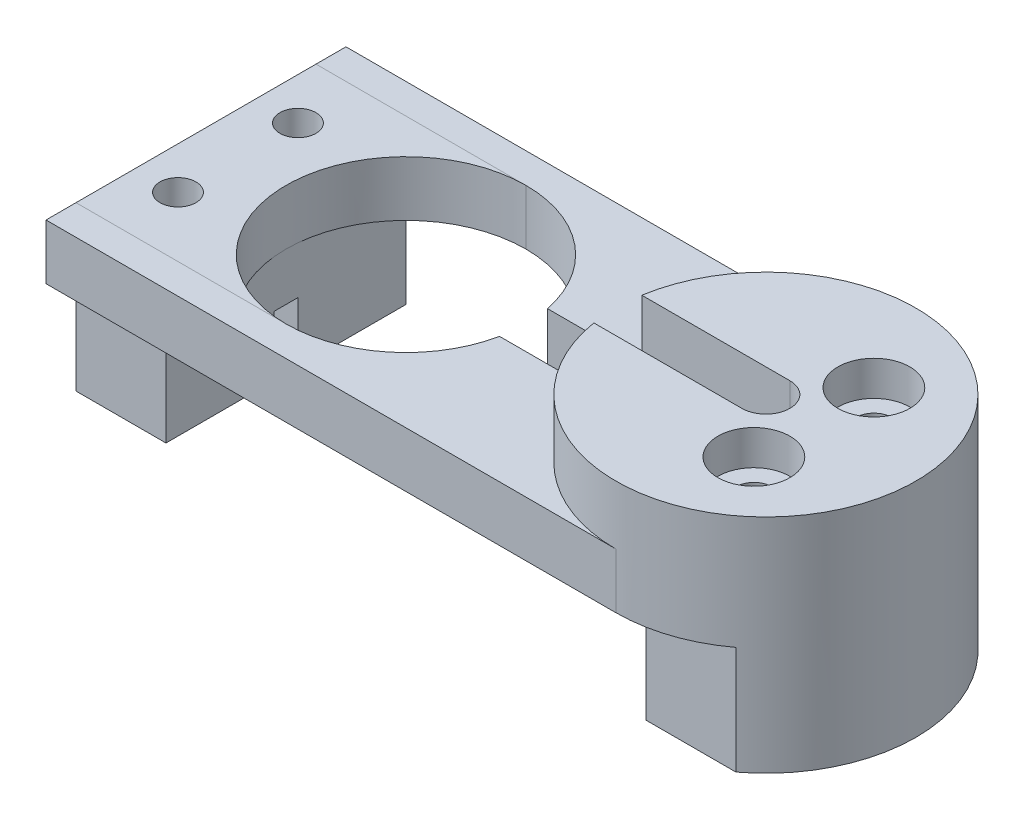
SolidWorks part; units mm, degrees
ref_plane "前视基准面" through (0, 0, 0) normal (0, 0, 1) x (1, 0, 0)
ref_plane "上视基准面" through (0, 0, 0) normal (0, 1, 0) x (1, 0, 0)
ref_plane "右视基准面" through (0, 0, 0) normal (1, 0, 0) x (0, 0, -1)
other "Configuration Table"
sketch "草图1" plane through (0, 0, 0) normal (0, 1, 0) x (1, 0, 0)
  line L0 (-20, 0) -> (20, 0) construction
  line L1 (-20, 10) -> (20, 10)
  line L2 (-20, 10) -> (-20, -10)
  line L3 (-20, -10) -> (20, -10)
  line L4 (20, 10) -> (20, -10)
  line L5 (-20, 10) -> (20, -10) construction
  line L6 (-20, -10) -> (20, 10) construction
  point P0 (0, 0)
  dimension "D1" = 40
  dimension "D2" = 20
extrude "凸台-拉伸1" add sketch "草图1" along normal blind 4.6
sketch "草图2" plane through (0, 0, 0) normal (0, -1, 0) x (1, 0, 0)
  line L0 (-20, 0) -> (20, 0) construction
  line L1 (-20, -10) -> (-20, 10) construction
  line L2 (20, 10) -> (20, -10) construction
  circle A0 centre (-10, 0) radius 6.5
  dimension "D1" = 13
  dimension "D2" = 10
extrude "切除-拉伸1" cut sketch "草图2" against normal blind 2
sketch "草图4" plane through (0, 2, 0) normal (0, -1, 0) x (1, 0, 0)
  circle A0 centre (-10, 0) radius 5.5
  dimension "D1" = 11
extrude "切除-拉伸5" cut sketch "草图4" against normal blind 2.6
sketch "草图5" plane through (0, 0, 0) normal (0, -1, 0) x (1, 0, 0)
  line L0 (20, 10) -> (20, -10) construction
  circle A0 centre (20, 0) radius 12.5
  dimension "D1" = 25
extrude "凸台-拉伸2" add sketch "草图5" against normal blind 9.5
sketch "草图6" plane through (0, 0, 0) normal (0, -1, 0) x (1, 0, 0)
  circle A0 centre (20, 0) radius 4.5
  dimension "D1" = 9
extrude "切除-拉伸6" cut sketch "草图6" against normal blind 4
sketch "草图7" plane through (0, 4, 0) normal (0, -1, 0) x (1, 0, 0)
  circle A0 centre (20, 0) radius 2
  dimension "D1" = 4
extrude "切除-拉伸7" cut sketch "草图7" against normal through all
sketch "草图8" plane through (0, 0, 0) normal (0, -1, 0) x (1, 0, 0)
  line L0 (20, -4.5) -> (20, -10) construction
  line L1 (-20, 10) -> (-27.5, 10)
  line L2 (-20, 10) -> (-20, -10)
  line L3 (-20, -10) -> (-27.5, -10)
  line L4 (-27.5, 10) -> (-27.5, -10)
  line L5 (12.5, 10) -> (20, 10) construction
  line L6 (12.5, 10) -> (12.5, -10) construction
  line L7 (12.5, -10) -> (20, -10) construction
  line L8 (20, 10) -> (20, 4.5) construction
  line L9 (20, -4.5) -> (20, -10)
  line L10 (20, 10) -> (27.5, 10)
  line L11 (20, 10) -> (20, 4.5)
  line L12 (20, -10) -> (27.5, -10)
  line L14 (-20, 0) -> (-27.5, 0) construction
  arc A1 (12.5, -10) -> (12.5, 10) centre (20, 0) ccw construction
  arc A2 (20, -4.5) -> (20, 4.5) centre (20, 0) ccw
  arc A3 (27.5, -10) -> (27.5, 10) centre (20, 0) ccw
  point P27 (-25, 0)
  dimension "D1" = 7.5
  dimension "D2" = 7.5
extrude "凸台-拉伸4" add sketch "草图8" along normal blind 9 and the other way blind 4.6
sketch "草图9" plane through (0, -9, 0) normal (0, -1, 0) x (1, 0, 0)
  line L0 (-27.5, 0) -> (-20, 0) construction
  line L1 (-25, 1) -> (-20, 1)
  line L2 (-25, 1) -> (-25, -1)
  line L3 (-25, -1) -> (-20, -1)
  line L4 (-20, 1) -> (-20, -1)
  line L5 (-27.5, 10) -> (-27.5, -10) construction
  line L7 (-20, -10) -> (-20, 10) construction
  line L8 (-20, 10) -> (20, 10)
  line L9 (20, 10) -> (20, 4.5) construction
  line L10 (0, 10) -> (0, 0) construction
  line L11 (25, -1) -> (20, -1)
  line L12 (20, 1) -> (20, -1)
  line L13 (25, 1) -> (20, 1)
  line L14 (25, 1) -> (25, -1)
  point P8 (-25, 0)
  line M7 (-20, -10) -> (-20, 10)
  dimension "D1" = 5
  dimension "D2" = 2
extrude "切除-拉伸8" cut sketch "草图9" against normal blind 5 contours L2 L3 L1 M7 | L14 L13 L12 L11
sketch "草图10" plane through (0, -9, 0) normal (0, -1, 0) x (1, 0, 0)
  line L0 (-20, -10) -> (-20, 10) construction
  line L1 (-20, -10) -> (-20, 10) construction
  line L2 (-20, 0) -> (-27.5, 0) construction
  line L3 (-27.5, 10) -> (-27.5, -10) construction
  line L4 (-20, 10) -> (20, 10)
  line L5 (0, 10) -> (0, 0) construction
  circle A0 centre (-24, 5) radius 1.5
  circle A1 centre (-24, -5) radius 1.5
  circle A2 centre (24, -5) radius 1.5
  circle A3 centre (24, 5) radius 1.5
  point P4 (-20, 0)
  dimension "D1" = 5
  dimension "D3" = 3
  dimension "D2" = 4
extrude "切除-拉伸9" cut sketch "草图10" against normal through all contours A0 | A1 | A2 | A3
sketch "草图13" plane through (0, 9.5, 0) normal (0, 1, 0) x (1, 0, 0)
  circle A0 centre (24, -5) radius 3
  circle A1 centre (24, 5) radius 3
  dimension "D1" = 6
  dimension "D2" = 6
extrude "切除-拉伸10" cut sketch "草图13" against normal blind 2.9
sketch "草图14" plane through (0, 9.5, 0) normal (0, 1, 0) x (1, 0, 0)
  line L0 (20, 2) -> (-4.8765, 2)
  line L1 (20, 2) -> (20, -2)
  line L2 (20, -2) -> (-4.8765, -2)
  line L3 (-4.8765, -2) -> (-4.8765, 2)
  circle A0 centre (20, 0) radius 2 construction
  circle A1 centre (-10, 0) radius 5.5 construction
extrude "切除-拉伸11" cut sketch "草图14" along direction (0, 1, 0) on the side against the normal up to next (9.5 mm away)
sketch "草图15" plane through (0, 4.6, 0) normal (0, 1, 0) x (1, 0, 0)
  circle A0 centre (-10, 0) radius 10
  dimension "D1" = 20
extrude "切除-拉伸14" cut sketch "草图15" against normal blind 5
sketch "草图16" plane through (0, 4.6, 0) normal (0, 1, 0) x (1, 0, 0)
  line L0 (-27.5, 0) -> (-19, 0) construction
  line L1 (-27.5, -10) -> (-27.5, 10) construction
  line L2 (20, 12.5) -> (-27.5, 12.5)
  line L3 (-27.5, 12.5) -> (-27.5, 10)
  line L4 (-27.5, 10) -> (12.5, 10)
  line L5 (20, -12.5) -> (-27.5, -12.5)
  line L6 (-27.5, -12.5) -> (-27.5, -10)
  line L7 (-27.5, -10) -> (12.5, -10)
  arc A1 (7.661, -2) -> (7.661, 2) centre (20, 0) ccw construction
  arc A2 (20, 12.5) -> (12.5, 10) centre (20, 0) ccw
  arc A3 (20, -12.5) -> (12.5, -10) centre (20, 0) cw
extrude "凸台-拉伸5" add sketch "草图16" against normal blind 4.6
